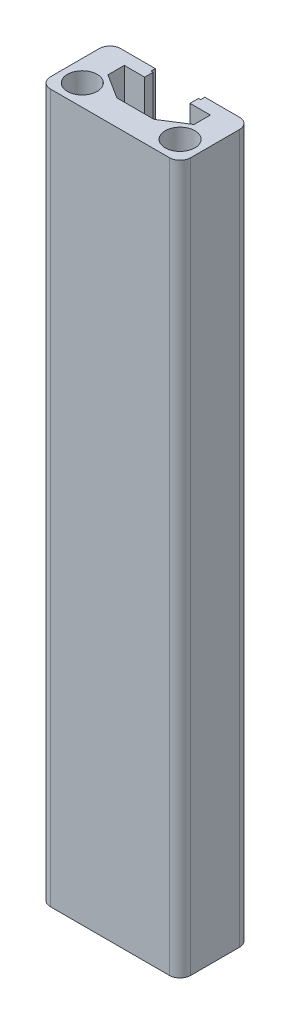
SolidWorks part; units mm, degrees
ref_plane "前视基准面" through (0, 0, 0) normal (0, 0, 1) x (1, 0, 0)
ref_plane "上视基准面" through (0, 0, 0) normal (0, 1, 0) x (1, 0, 0)
ref_plane "右视基准面" through (0, 0, 0) normal (1, 0, 0) x (0, 0, -1)
other "Configuration Table"
sketch "草图1" plane through (0, 0, 0) normal (0, 1, 0) x (1, 0, 0)
  line L0 (0, 0) -> (0, 6868.258) construction
  line L1 (8.4, 0) -> (-8.4, 0)
  line L2 (-9.9, 1.5) -> (-9.9, 8.4)
  line L3 (-8.4, 9.9) -> (-3.5, 9.9)
  line L4 (-3.5, 9.9) -> (-3.5, 9.2885)
  line L5 (-3.5, 9.2885) -> (-3.2, 9.2885)
  line L6 (-3.2, 9.2885) -> (-3.2, 8.1)
  line L7 (-3.2, 8.1) -> (-6.0748, 8.1)
  line L8 (-6.0748, 8.1) -> (-6.0748, 5.793)
  line L9 (-6.0748, 5.793) -> (-2.6166, 3.6)
  line L10 (-2.6166, 3.6) -> (2.6166, 3.6)
  line L11 (6.0748, 5.793) -> (2.6166, 3.6)
  line L12 (6.0748, 8.1) -> (6.0748, 5.793)
  line L13 (3.2, 8.1) -> (6.0748, 8.1)
  line L14 (3.2, 9.2885) -> (3.2, 8.1)
  line L15 (3.5, 9.2885) -> (3.2, 9.2885)
  line L16 (3.5, 9.9) -> (3.5, 9.2885)
  line L17 (8.4, 9.9) -> (3.5, 9.9)
  line L18 (9.9, 1.5) -> (9.9, 8.4)
  circle A0 centre (-6.9, 3) radius 2.1
  arc A1 (9.9, 1.5) -> (8.4, 0) centre (8.4, 1.5) cw
  arc A2 (8.4, 9.9) -> (9.9, 8.4) centre (8.4, 8.4) cw
  arc A3 (-8.4, 0) -> (-9.9, 1.5) centre (-8.4, 1.5) cw
  arc A4 (-9.9, 8.4) -> (-8.4, 9.9) centre (-8.4, 8.4) cw
  circle A5 centre (6.9, 3) radius 2.1
  point P15 (0, 3.6)
  point P23 (0, 0)
  point P27 (9.9, 0)
  point P30 (9.9, 9.9)
  point P33 (-9.9, 0)
  point P36 (-9.9, 9.9)
  dimension "D7" = 4.2
  dimension "D8" = 3
  dimension "D9" = 3
  dimension "D10" = 1.5
  dimension "D1" = 19.8
  dimension "D2" = 9.9
  dimension "D3" = 7
  dimension "D4" = 6.4
  dimension "D5" = 6.3
  dimension "D6" = 1.8
extrude "凸台-拉伸1" add sketch "草图1" along normal blind 100
